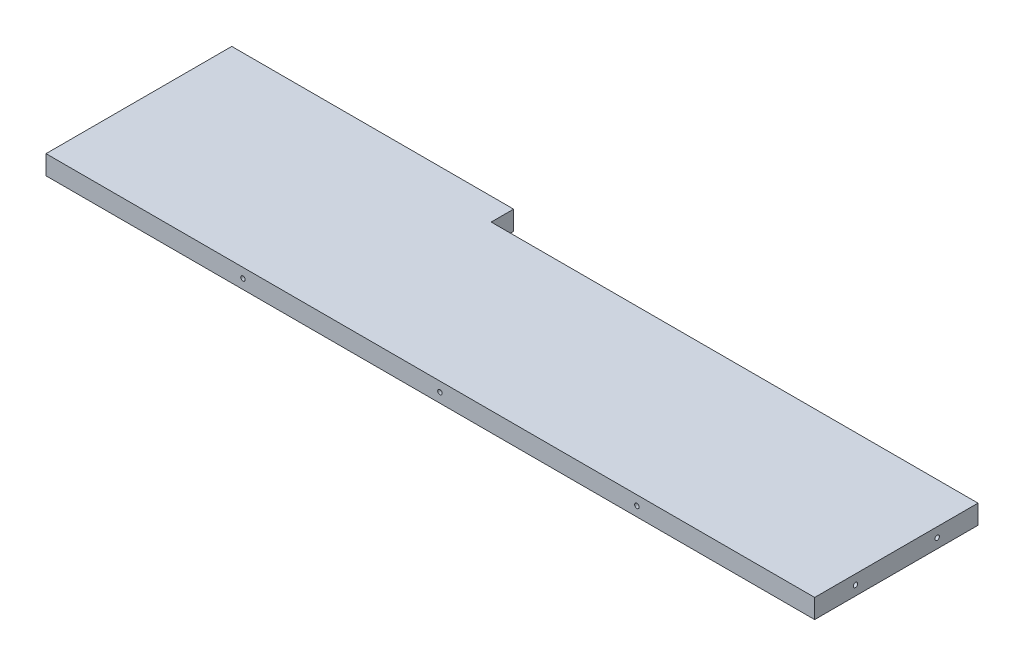
SolidWorks part; units mm, degrees
ref_plane "前视基准面" through (0, 0, 0) normal (0, 0, 1) x (1, 0, 0)
ref_plane "上视基准面" through (0, 0, 0) normal (0, 1, 0) x (1, 0, 0)
ref_plane "右视基准面" through (0, 0, 0) normal (1, 0, 0) x (0, 0, -1)
other "Configuration Table"
sketch "草图1" plane through (0, 0, 0) normal (0, 1, 0) x (1, 0, 0)
  line L1 (-60, -14.5) -> (60, -14.5)
  line L2 (-60, -14.5) -> (-60, 14.5)
  line L3 (-60, 14.5) -> (60, 14.5)
  line L4 (60, -14.5) -> (60, 14.5)
  line L5 (-60, -14.5) -> (60, 14.5) construction
  line L6 (-60, 14.5) -> (60, -14.5) construction
  point P0 (0, 0)
  dimension "D1" = 120
  dimension "D5" = 29
extrude "凸台-拉伸1" add sketch "草图1" along normal blind 3
sketch "草图2" plane through (0, 0, 0) normal (0, -1, 0) x (1, 0, 0)
  line L0 (60, 14.5) -> (60, -14.5) construction
  line L1 (-16, -11) -> (60, -11)
  line L2 (-16, -11) -> (-16, -14.5)
  line L3 (-16, -14.5) -> (60, -14.5)
  line L4 (60, -11) -> (60, -14.5)
  line L5 (-60, -14.5) -> (60, -14.5) construction
  dimension "D1" = 3.5
  dimension "D2" = 76
extrude "切除-拉伸1" cut sketch "草图2" against normal through all
sketch "草图3" plane through (60, 0, 0) normal (1, 0, 0) x (0, 0, -1)
  circle A0 centre (-8.125, 1.5) radius 0.35
  circle A1 centre (4.625, 1.5) radius 0.35
  point P4 (0, 0)
  dimension "D1" = 0.7
extrude "切除-拉伸2" cut sketch "草图3" against normal blind 3
sketch "草图5" plane through (0, 0, 14.5) normal (0, 0, 1) x (1, 0, 0)
  circle A0 centre (-29.25, 1.5) radius 0.35
  circle A1 centre (1.5, 1.5) radius 0.35
  circle A3 centre (32.25, 1.5) radius 0.35
  point P6 (0, 0)
  dimension "D1" = 0.7
extrude "切除-拉伸3" cut sketch "草图5" against normal blind 3
